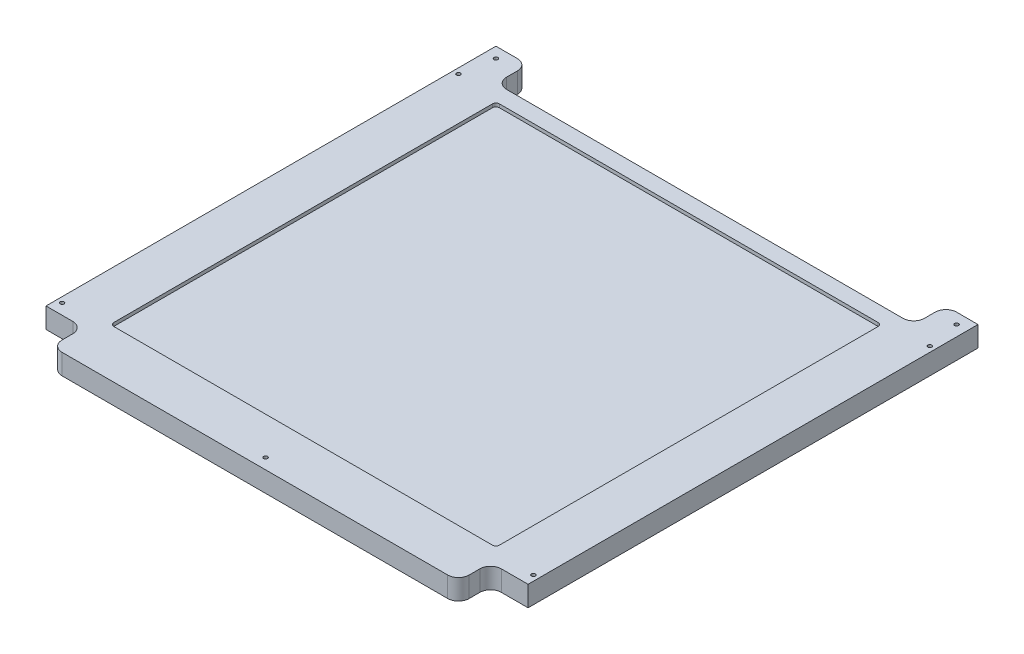
SolidWorks part; units mm, degrees
ref_plane "Front Plane" through (0, 0, 0) normal (0, 0, 1) x (1, 0, 0)
ref_plane "Top Plane" through (0, 0, 0) normal (0, 1, 0) x (1, 0, 0)
ref_plane "Right Plane" through (0, 0, 0) normal (1, 0, 0) x (0, 0, -1)
sketch "Sketch2" plane through (0, 0, 0) normal (0, 1, 0) x (1, 0, 0)
  line L1 (0, 0) -> (450, 0)
  line L2 (0, 0) -> (0, 450)
  line L3 (0, 450) -> (450, 450)
  line L4 (450, 0) -> (450, 450)
  dimension "D1" = 450
  dimension "D2" = 450
extrude "Boss-Extrude1" add sketch "Sketch2" along normal blind 19.05
sketch "Sketch7" plane through (0, 19.05, 0) normal (0, 1, 0) x (1, 0, 0)
  line L0 (225, 0) -> (225, 420) construction
  line L1 (0, 0) -> (450, 0) construction
  line L2 (450, 450) -> (0, 450) construction
  line L3 (415, 0) -> (415, 30)
  line L4 (0, 0) -> (35, 0)
  line L5 (0, 0) -> (0, 30)
  line L6 (0, 30) -> (35, 30)
  line L7 (35, 0) -> (35, 30)
  line L8 (30, 450) -> (420, 450)
  line L9 (30, 450) -> (30, 420)
  line L10 (30, 420) -> (420, 420)
  line L11 (450, 0) -> (415, 0)
  line L12 (450, 0) -> (450, 30)
  line L13 (450, 30) -> (415, 30)
  line L14 (420, 450) -> (420, 420)
  point P20 (225, 450)
  dimension "D1" = 390
  dimension "D2" = 35
  dimension "D3" = 30
  dimension "D4" = 30
extrude "Cut-Extrude2" cut sketch "Sketch7" against normal through all
fillet "Fillet2" radius 10 8 edges at (420, 9.525, -450) (420, 9.525, -420) (30, 9.525, -420) (30, 9.525, -450) (415, 9.525, -30) (415, 9.525, 0) (35, 9.525, 0) (35, 9.525, -30)
sketch "Sketch3" plane through (0, 19.05, 0) normal (0, 1, 0) x (1, 0, 0)
  line L0 (225, 420) -> (225, 0) construction
  line L1 (450, 450) -> (430, 450) construction
  line L2 (45, 0) -> (405, 0) construction
  line L3 (0, 225) -> (450, 225) construction
  line L4 (40, 420) -> (410, 420) construction
  line L6 (45, 45) -> (45, 405)
  line L7 (45, 405) -> (405, 405)
  line L8 (405, 45) -> (405, 405)
  line L9 (45, 45) -> (405, 45)
  line L10 (450, 30) -> (450, 450) construction
  line L11 (0, 450) -> (0, 30) construction
  point P17 (225, 405)
  point P18 (405, 225)
  point P19 (45, 225)
  dimension "D1" = 360
  dimension "D2" = 360
  dimension "D3" = 45
extrude "Cut-Extrude1" cut sketch "Sketch3" against normal blind 3.175
fillet "Fillet1" radius 3.175 4 edges at (45, 17.4625, -45) (405, 17.4625, -45) (405, 17.4625, -405) (45, 17.4625, -405)
hole_wizard "M3 Clearance Hole1" positions "3DSketch1" profile "Sketch4" hole size "M3" standard "ANSI Metric" end condition through all
sketch3d "3DSketch1"
  line L0 (450, 19.05, -440) -> (440, 19.05, -440) construction
  line L1 (450, 19.05, -30) -> (450, 19.05, -450) construction
  line L2 (440, 19.05, -440) -> (440, 19.05, -450) construction
  line L3 (450, 19.05, -450) -> (430, 19.05, -450) construction
  line L5 (0, 19.05, -440) -> (10, 19.05, -440) construction
  line L6 (0, 19.05, -450) -> (0, 19.05, -30) construction
  line L7 (10, 19.05, -440) -> (10, 19.05, -450) construction
  line L9 (225, 19.05, 0) -> (225, 19.05, -420) construction
  line L10 (45, 19.05, 0) -> (405, 19.05, 0) construction
  line L11 (40, 19.05, -420) -> (410, 19.05, -420) construction
  line L12 (45, 19.05, 0) -> (405, 19.05, 0) construction
  point P0 (440, 19.05, -440)
  point P2 (10, 19.05, -440)
  point P4 (225, 19.05, -10)
  point P37 (0, 0, 0)
  dimension "D1" = 10
  dimension "D2" = 10
  dimension "D3" = 10
sketch "Sketch4" plane through (440, 19.05, -440) normal (1, 0, 0) x (0, 0, 1)
  line L0 (0, 0) -> (0, 19.05)
  line L1 (0, 19.05) -> (1.8, 19.05)
  line L2 (1.8, 19.05) -> (1.8, 0)
  line L5 (1.8, 0) -> (0, 0)
  line L11 (0, -6.35) -> (0, 107.95) construction
  dimension "Thru Hole Dia." = 3.6
  dimension "Thru Hole Depth" = 19.05
hole_wizard "M3 Clearance Hole2" positions "3DSketch2" profile "Sketch5" hole size "M3" standard "ANSI Metric" end condition through all
sketch3d "3DSketch2"
  line L0 (445, 19.05, -410) -> (445, 19.05, -40) construction
  line L3 (5, 19.05, -410) -> (5, 19.05, -40) construction
  line L7 (450, 19.05, -30) -> (450, 19.05, -450) construction
  line L8 (0, 19.05, -450) -> (0, 19.05, -30) construction
  line L9 (450, 19.05, -30) -> (425, 19.05, -30) construction
  line L10 (40, 19.05, -420) -> (410, 19.05, -420) construction
  point P0 (445, 19.05, -410)
  point P2 (5, 19.05, -410)
  point P4 (5, 19.05, -40)
  point P6 (445, 19.05, -40)
  dimension "D1" = 10
  dimension "D2" = 5
  dimension "D3" = 5
  dimension "D4" = 10
sketch "Sketch5" plane through (445, 19.05, -410) normal (1, 0, 0) x (0, 0, 1)
  line L0 (0, 0) -> (0, 19.05)
  line L1 (0, 19.05) -> (1.8, 19.05)
  line L2 (1.8, 19.05) -> (1.8, 0)
  line L5 (1.8, 0) -> (0, 0)
  line L11 (0, -6.35) -> (0, 107.95) construction
  dimension "Thru Hole Dia." = 3.6
  dimension "Thru Hole Depth" = 19.05
